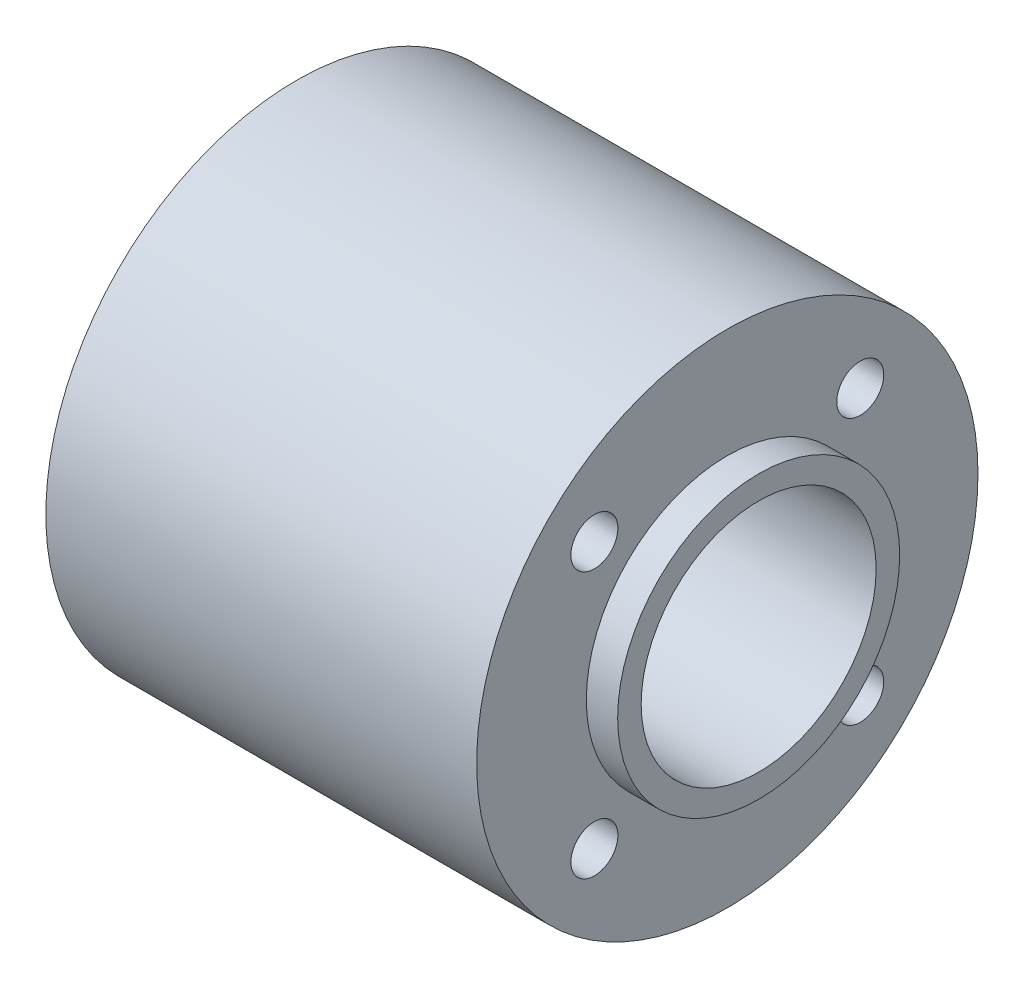
SolidWorks part; units mm, degrees
ref_plane "前视基准面" through (0, 0, 0) normal (0, 0, 1) x (1, 0, 0)
ref_plane "上视基准面" through (0, 0, 0) normal (0, 1, 0) x (1, 0, 0)
ref_plane "右视基准面" through (0, 0, 0) normal (1, 0, 0) x (0, 0, -1)
sketch "草图1" plane through (0, 0, 0) normal (1, 0, 0) x (0, 0, -1)
  line L0 (0, 0) -> (0, 16) construction
  line L1 (0, 0) -> (-8.4853, 8.4853) construction
  circle A0 centre (0, 0) radius 16
  circle A1 centre (0, 0) radius 12 construction
  circle A2 centre (0, 0) radius 7.5
  circle A3 centre (-8.4853, 8.4853) radius 1.5
  circle A4 centre (8.4853, 8.4853) radius 1.5
  circle A5 centre (8.4853, -8.4853) radius 1.5
  circle A6 centre (-8.4853, -8.4853) radius 1.5
  point P17 (0, 0)
  dimension "D1" = 32
  dimension "D2" = 24
  dimension "D3" = 15
  dimension "D5" = 3
  dimension "D4" = 45
  dimension "D6" = 4
extrude "凸台-拉伸1" add sketch "草图1" along normal mid plane 27.5
sketch "草图5" plane through (-13.75, 0, 0) normal (-1, 0, 0) x (0, 0, 1)
  circle A0 centre (0, 0) radius 9
  circle M3 centre (0, 0) radius 7.5
  dimension "D1" = 18
extrude "凸台-拉伸6" [suppressed] add sketch "草图5" along normal blind 2 contours A0 M3
sketch "草图6" plane through (13.75, 0, 0) normal (1, 0, 0) x (0, 0, -1)
  circle A0 centre (0, 0) radius 9
  circle M4 centre (0, 0) radius 7.5
  dimension "D1" = 18
extrude "凸台-拉伸7" add sketch "草图6" along normal blind 2 contours A0 M4
mirror "镜向2" about plane through (0, 0, 0) normal (1, 0, 0) of "凸台-拉伸7"
